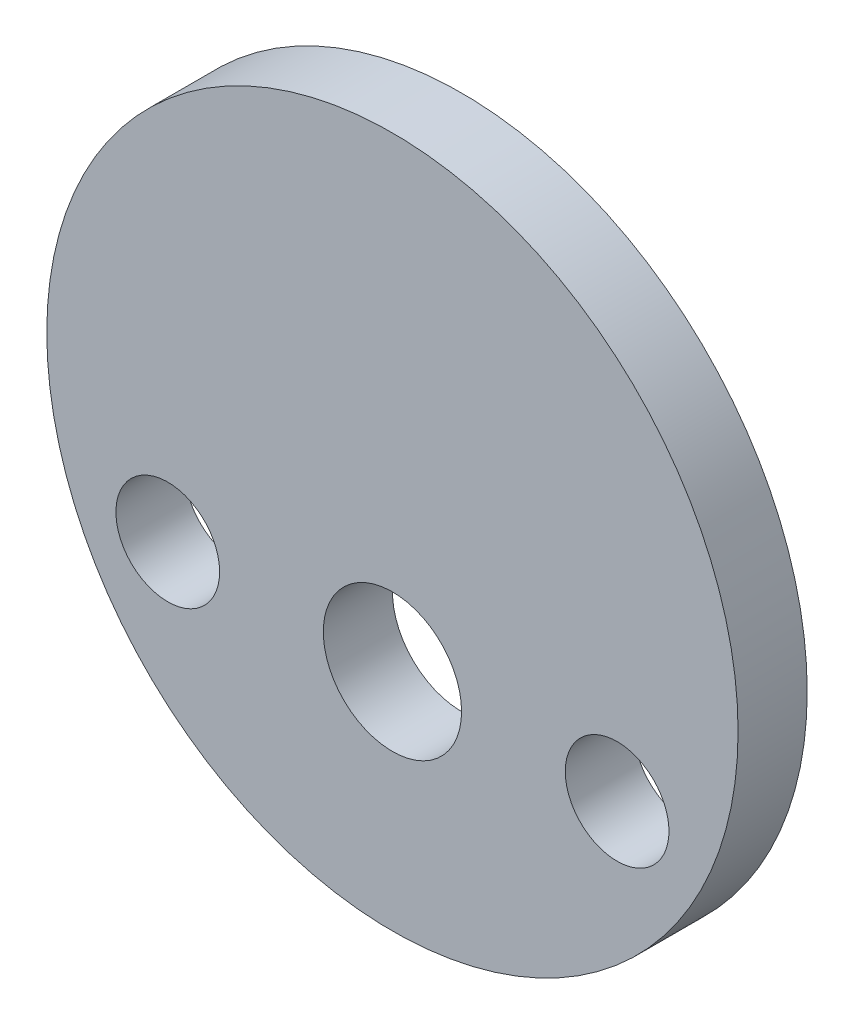
SolidWorks part; units mm, degrees
ref_plane "前视基准面" through (0, 0, 0) normal (0, 0, 1) x (1, 0, 0)
ref_plane "上视基准面" through (0, 0, 0) normal (0, 1, 0) x (1, 0, 0)
ref_plane "右视基准面" through (0, 0, 0) normal (1, 0, 0) x (0, 0, -1)
sketch "草图1" plane through (0, 0, 0) normal (0, 0, 1) x (1, 0, 0)
  line L0 (-0.5899, 5.3428) -> (-0.5899, 1.8428) construction
  line L1 (-0.5899, 1.8428) -> (-7.0899, 1.8428) construction
  circle A1 centre (-7.0899, 1.8428) radius 1.5
  circle A2 centre (5.9101, 1.8428) radius 1.5
  circle A3 centre (-0.5899, 1.8428) radius 2
  circle A4 centre (-0.5899, 5.3428) radius 10
  dimension "D1" = 3.5
  dimension "D2" = 6.5
extrude "凸台-拉伸1" add sketch "草图1" along normal blind 2 contours A4
